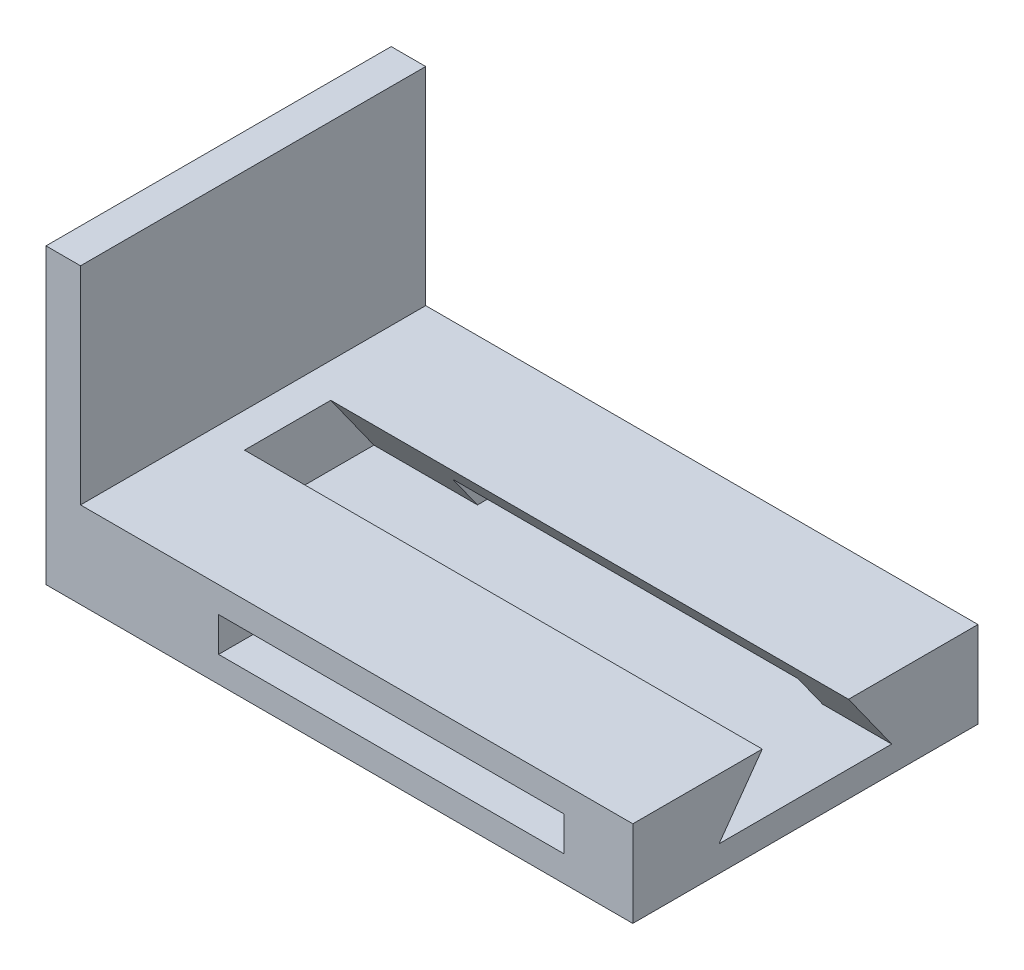
SolidWorks part; units mm, degrees
ref_plane "Front Plane" through (0, 0, 0) normal (0, 0, 1) x (1, 0, 0)
ref_plane "Top Plane" through (0, 0, 0) normal (0, 1, 0) x (1, 0, 0)
ref_plane "Right Plane" through (0, 0, 0) normal (1, 0, 0) x (0, 0, -1)
sketch "Sketch3" plane through (0, 0, 0) normal (1, 0, 0) x (0, 0, -1)
  line L1 (0, 0) -> (20, 0)
  line L2 (0, 0) -> (0, -12)
  line L3 (0, -12) -> (20, -12)
  line L4 (20, 0) -> (20, -12)
  dimension "D1" = 20
  dimension "D2" = 12
extrude "Boss-Extrude3" add sketch "Sketch3" along normal blind 2
sketch "Sketch4" plane through (2, 0, 0) normal (1, 0, 0) x (0, 0, -1)
  line L0 (0, -12) -> (20, -12) construction
  line L6 (0, -12) -> (20, -12)
  line L8 (0, -12) -> (0, -17)
  line L9 (0, -17) -> (20, -17)
  line L10 (20, -12) -> (20, -17)
  dimension "D1" = 20
  dimension "D4" = 5
extrude "Boss-Extrude5" add sketch "Sketch4" along normal blind 32 and the other way blind 2
sketch "Sketch6" plane through (34, 0, 0) normal (1, 0, 0) x (0, 0, -1)
  line L0 (10, -17) -> (10, -15.5) construction
  line L4 (5, -15.5) -> (15, -15.5)
  line L7 (0, -17) -> (20, -17) construction
  line L8 (10, -15.5) -> (10, -12) construction
  line L9 (20, -12) -> (0, -12) construction
  line L10 (7.5, -12) -> (12.5, -12)
  line L11 (5, -15.5) -> (7.5, -12)
  line L12 (12.5, -12) -> (15, -15.5)
  point P12 (10, -12)
  dimension "D1" = 5
  dimension "D3" = 10
  dimension "D4" = 3.5
extrude "Cut-Extrude1" cut sketch "Sketch6" against normal blind 30
sketch "Sketch7" plane through (0, 0, -20) normal (0, 0, -1) x (-1, 0, 0)
  line L0 (-34, -17) -> (-34, -12) construction
  line L5 (-10, -13.5) -> (-30, -13.5)
  line L6 (-10, -13.5) -> (-10, -15.5)
  line L7 (-10, -15.5) -> (-30, -15.5)
  line L8 (-30, -13.5) -> (-30, -15.5)
  line L10 (-2, -12) -> (-34, -12) construction
  dimension "D1" = 2
  dimension "D2" = 4
  dimension "D4" = 1.5
  dimension "D6" = 20
extrude "Cut-Extrude2" cut sketch "Sketch7" against normal through all
